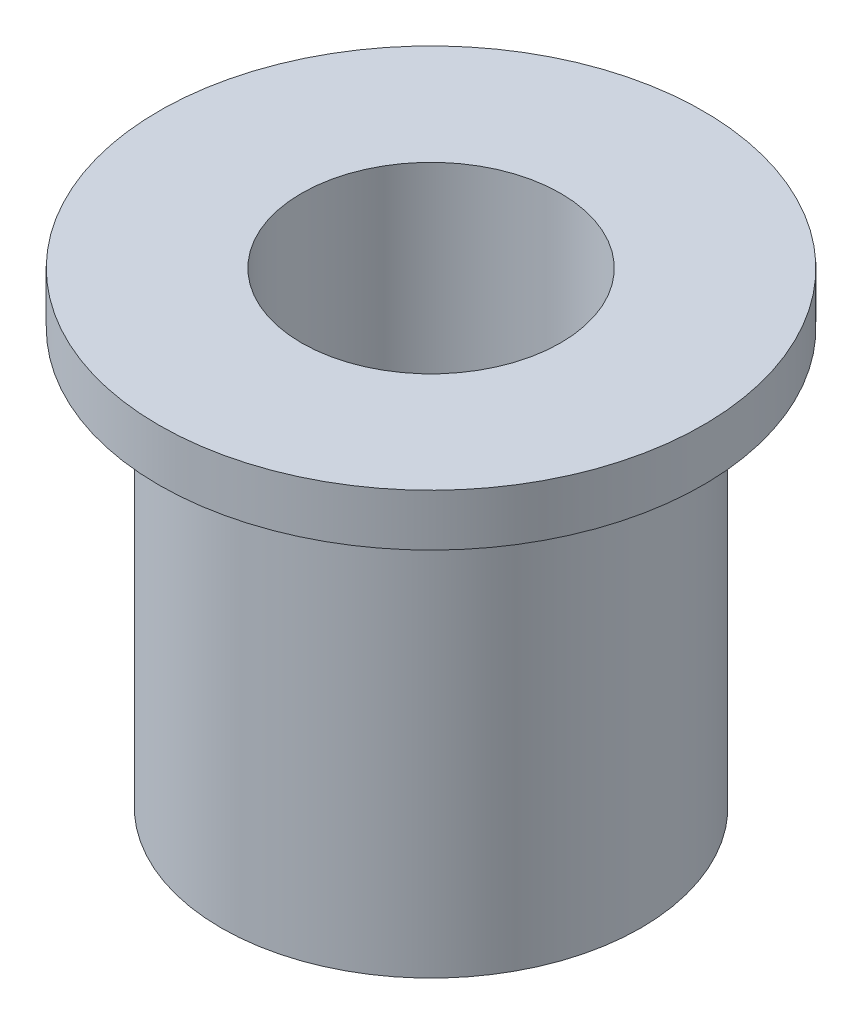
SolidWorks part; units mm, degrees
ref_plane "Front Plane" through (0, 0, 0) normal (0, 0, 1) x (1, 0, 0)
ref_plane "Top Plane" through (0, 0, 0) normal (0, 1, 0) x (1, 0, 0)
ref_plane "Right Plane" through (0, 0, 0) normal (1, 0, 0) x (0, 0, -1)
sketch "Sketch1" plane through (0, 0, 0) normal (0, 1, 0) x (1, 0, 0)
  circle A0 centre (0, 0) radius 2.5
  circle A1 centre (0, 0) radius 4.05
  dimension "D1" = 8.1
  dimension "D2" = 5
extrude "Boss-Extrude1" add sketch "Sketch1" along normal blind 9
sketch "Sketch2" plane through (0, 9, 0) normal (0, 1, 0) x (1, 0, 0)
  circle A0 centre (0, 0) radius 5.25
  circle A2 centre (0, 0) radius 2.5 construction
  circle A3 centre (0, 0) radius 2.5
  dimension "D1" = 10.5
extrude "Boss-Extrude2" add sketch "Sketch2" against normal blind 1
sketch "Sketch3" plane through (0, 0, 0) normal (0, -1, 0) x (1, 0, 0)
  circle A2 centre (0, 0) radius 3.5
  circle A3 centre (0, 0) radius 3.1
  dimension "D1" = 0.4
  dimension "D2" = 7
extrude "Cut-Extrude1" cut sketch "Sketch3" against normal blind 4.5
